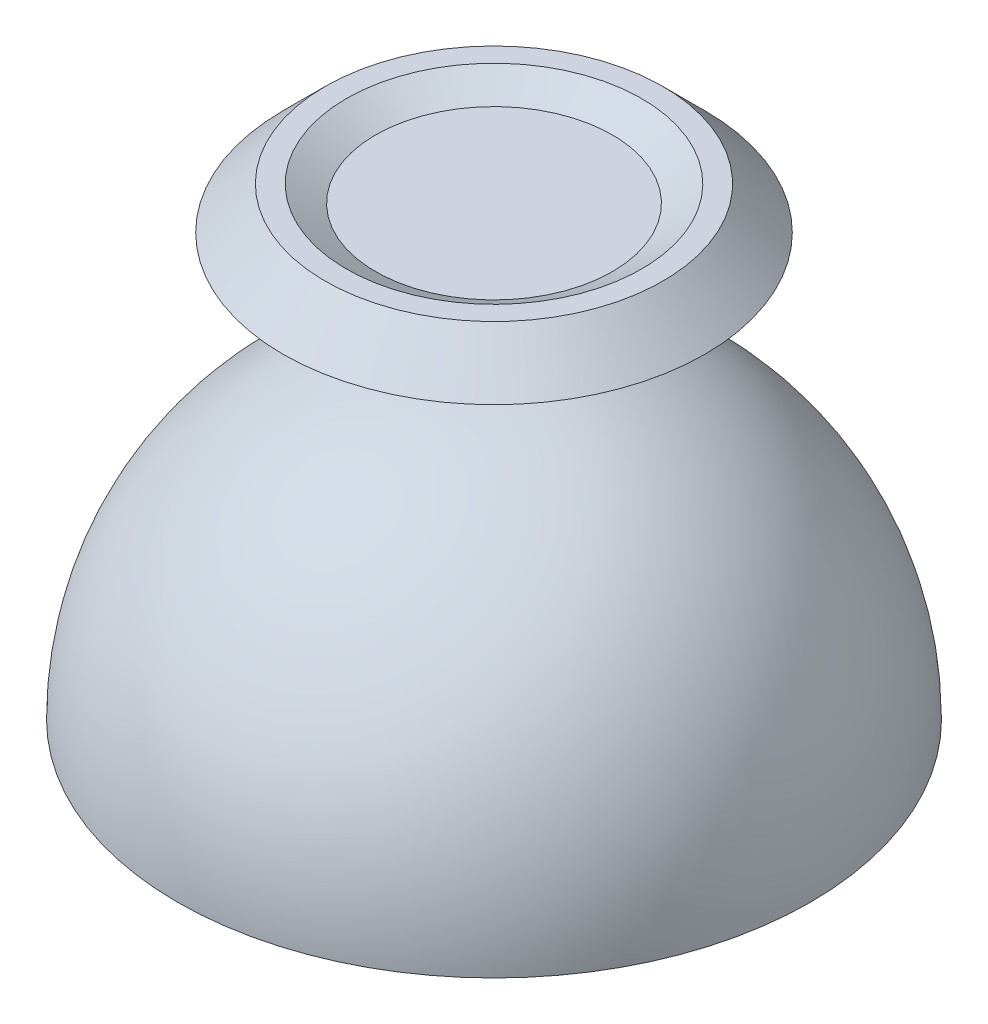
SolidWorks part; units mm, degrees
ref_plane "Front Plane" through (0, 0, 0) normal (0, 0, 1) x (1, 0, 0)
ref_plane "Top Plane" through (0, 0, 0) normal (0, 1, 0) x (1, 0, 0)
ref_plane "Right Plane" through (0, 0, 0) normal (1, 0, 0) x (0, 0, -1)
sketch "Sketch1" plane through (0, 0, 0) normal (0, 1, 0) x (1, 0, 0)
  line L1 (0, -14) -> (0, -15)
  line L2 (0, 14) -> (0, 15)
  arc A0 (0, 15) -> (0, -15) centre (0, 0) ccw
  arc A1 (0, 14) -> (0, -14) centre (0, 0) ccw
revolve "Revolve2" add sketch "Sketch1" angle 180 about L2
ref_plane "Plane1" through (0, 6, 0) normal (0, -1, 0) x (-1, 0, 0)
sketch "Sketch3" plane through (0, 6, 0) normal (0, -1, 0) x (-1, 0, 0)
  line L1 (-1.1, -0.75) -> (1.1, -0.75)
  line L2 (-1.1, -0.75) -> (-1.1, 0.75)
  line L3 (-1.1, 0.75) -> (1.1, 0.75)
  line L4 (1.1, -0.75) -> (1.1, 0.75)
  line L5 (-1.1, -0.75) -> (1.1, 0.75) construction
  line L6 (-1.1, 0.75) -> (1.1, -0.75) construction
  point P0 (0, 0)
  dimension "D1" = 1.5
  dimension "D2" = 2.2
ref_plane "Plane3" through (0, 15, 0) normal (0, 1, 0) x (1, 0, 0)
ref_plane "Plane4" through (0, 20, 0) normal (0, 1, 0) x (1, 0, 0)
sketch "Sketch6" plane through (0, 20, 0) normal (0, 1, 0) x (1, 0, 0)
  circle A0 centre (0, 0) radius 2.25
extrude "Boss-Extrude4" add sketch "Sketch6" against normal up to surface (5.1697 mm away)
sketch "Sketch7" plane through (0, 20, 0) normal (0, 1, 0) x (1, 0, 0)
  circle A1 centre (0, 0) radius 10
extrude "Boss-Extrude6" add sketch "Sketch7" along normal blind 2 draft 45
sketch "Sketch8" plane through (0, 22, 0) normal (0, 1, 0) x (1, 0, 0)
  circle A0 centre (0, 0) radius 7
extrude "Cut-Extrude1" cut sketch "Sketch8" against normal blind 0.8 draft 60
extrude "Cut-Extrude4" cut sketch "Sketch3" against normal blind 8
sketch "Sketch10" plane through (0, 6, 0) normal (0, -1, 0) x (-1, 0, 0)
  line L1 (-1.1, -0.75) -> (1.1, -0.75)
  line L2 (-1.1, -0.75) -> (-1.1, 0.75)
  line L3 (-1.1, 0.75) -> (1.1, 0.75)
  line L4 (1.1, -0.75) -> (1.1, 0.75)
  line L5 (-1.1, -0.75) -> (1.1, 0.75) construction
  line L6 (-1.1, 0.75) -> (1.1, -0.75) construction
  circle A0 centre (0, 0) radius 2.25
extrude "Boss-Extrude7" add sketch "Sketch10" against normal up to surface (7.818 mm away)
ref_plane "Plane6" through (-2.25, 0, 0) normal (-1, 0, 0) x (0, 0, 1)
sketch "Sketch12" plane through (-2.25, 0, 0) normal (-1, 0, 0) x (0, 0, 1)
  line L1 (0.3674, 13.8071) -> (-0.3674, 13.8071)
  line L2 (0.3674, 13.8071) -> (0.3674, 10.3071)
  line L3 (0.3674, 10.3071) -> (-0.3674, 10.3071)
  line L4 (-0.3674, 13.8071) -> (-0.3674, 10.3071)
  line L5 (0.3674, 13.8071) -> (-0.3674, 10.3071) construction
  line L6 (0.3674, 10.3071) -> (-0.3674, 13.8071) construction
  point P0 (0, 12.0571)
extrude "Boss-Extrude9" add sketch "Sketch12" along normal up to surface and the other way up to surface up to face at (2.25, 13.818, 0) other way up to face at (2.25, 6, 0)
pattern_circular "CirPattern1" count 6 over 360 about axis through (0, 0, 0) along (0, 1, 0) of "Boss-Extrude9"
